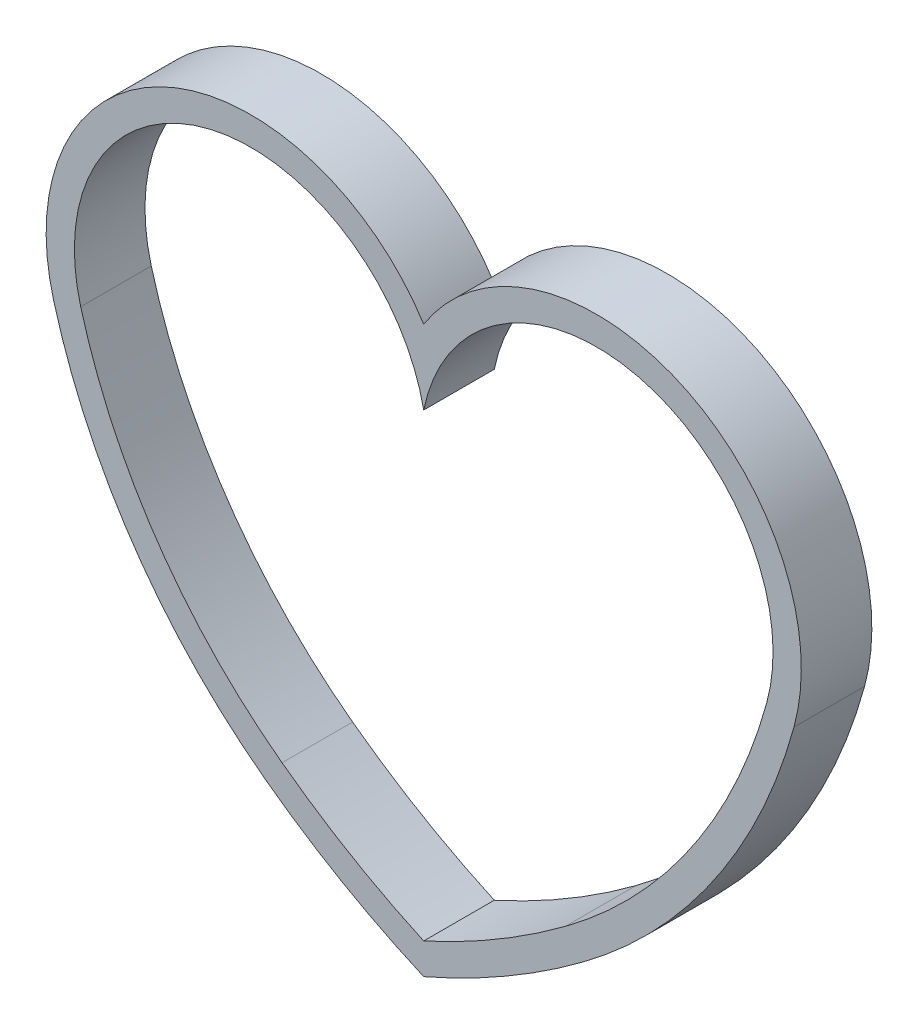
SolidWorks part; units mm, degrees
material "Copper"
ref_plane "Front Plane" through (0, 0, 0) normal (0, 0, 1) x (1, 0, 0)
ref_plane "Top Plane" through (0, 0, 0) normal (0, 1, 0) x (1, 0, 0)
ref_plane "Right Plane" through (0, 0, 0) normal (1, 0, 0) x (0, 0, -1)
sketch "Sketch1" plane through (0, 0, 0) normal (0, 0, 1) x (1, 0, 0)
  line L0 (0, 108.7272) -> (0, -129.3504) construction
  arc A0 (12.3449, -2.9521) -> (0, 0) centre (6.2217, -1.27) ccw
  arc A1 (0, -16.5472) -> (5.0986, -13.5419) centre (-11.5583, 8.89) ccw
  arc A2 (5.0986, -13.5419) -> (12.3449, -2.9521) centre (-6.6369, 2.2624) ccw
  arc A3 (0, -16.5472) -> (-5.0986, -13.5419) centre (11.5583, 8.89) cw
  arc A4 (-5.0986, -13.5419) -> (-12.3449, -2.9521) centre (6.6369, 2.2624) cw
  arc A5 (-12.3449, -2.9521) -> (0, 0) centre (-6.2217, -1.27) cw
  arc A6 (-13.3246, -3.2212) -> (0, 2.6731) centre (-6.2217, -1.27) cw
  arc A7 (13.3246, -3.2212) -> (0, 2.6731) centre (6.2217, -1.27) ccw
  arc A8 (5.7043, -14.3576) -> (13.3246, -3.2212) centre (-6.6369, 2.2624) ccw
  arc A9 (0, -17.6591) -> (5.7043, -14.3576) centre (-11.5583, 8.89) ccw
  arc A10 (0, -17.6591) -> (-5.7043, -14.3576) centre (11.5583, 8.89) cw
  arc A11 (-5.7043, -14.3576) -> (-13.3246, -3.2212) centre (6.6369, 2.2624) cw
  dimension "D2" = 12.7
  dimension "D3" = 55.88
  dimension "D6" = 39.37
  dimension "D1" = 1.27
  dimension "D4" = 17.78
  dimension "D5" = 10.16
  dimension "D7" = 1.016
extrude "Boss-Extrude1" add sketch "Sketch1" along normal blind 2.54
